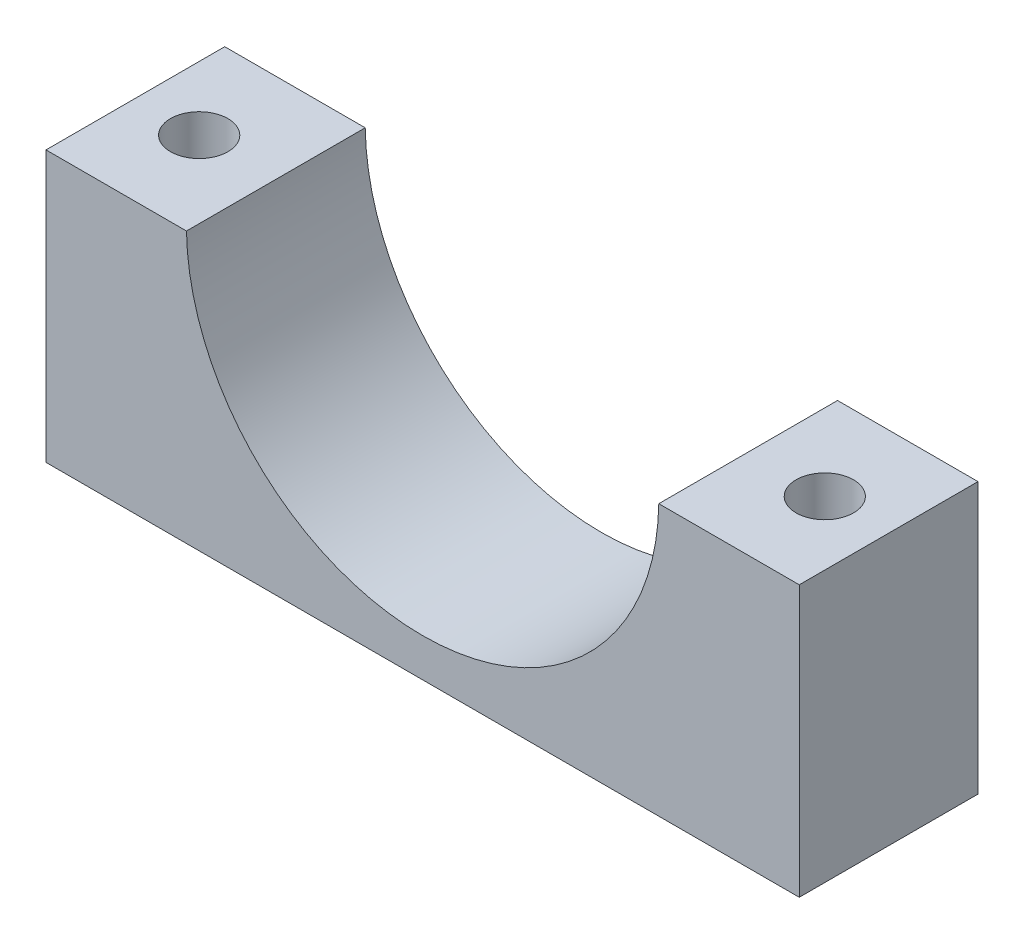
SolidWorks part; units mm, degrees
ref_plane "Front Plane" through (0, 0, 0) normal (0, 0, 1) x (1, 0, 0)
ref_plane "Top Plane" through (0, 0, 0) normal (0, 1, 0) x (1, 0, 0)
ref_plane "Right Plane" through (0, 0, 0) normal (1, 0, 0) x (0, 0, -1)
sketch "Split saddle with 37.0 mm prototype bore profile" plane through (0, 0, 0) normal (0, 0, 1) x (1, 0, 0)
  line L0 (-29.5, 7) -> (29.5, 7)
  line L1 (29.5, 7) -> (29.5, 28.2)
  line L2 (29.5, 28.2) -> (18.4976, 28.2)
  line L3 (-18.4976, 28.2) -> (-29.5, 28.2)
  line L4 (-29.5, 28.2) -> (-29.5, 7)
  arc A0 (18.4976, 28.2) -> (-18.4976, 28.2) centre (0, 28.5) cw
extrude "Split saddle with 37.0 mm prototype bore" add sketch "Split saddle with 37.0 mm prototype bore profile" along normal blind 14
sketch "Sketch2" plane through (0, 0, 0) normal (0, 1, 0) x (1, 0, 0)
  circle A0 centre (-24.5, -7) radius 2.25
  circle A1 centre (24.5, -7) radius 2.25
extrude "M4 through holes" cut sketch "Sketch2" against normal through all and the other way through all
